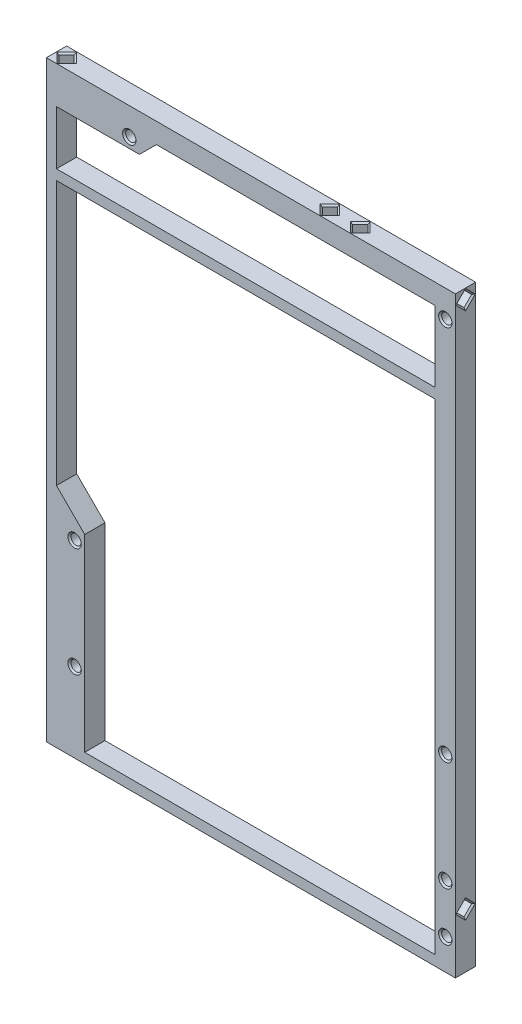
SolidWorks part; units mm, degrees
ref_plane "Front Plane" through (0, 0, 0) normal (0, 0, 1) x (1, 0, 0)
ref_plane "Top Plane" through (0, 0, 0) normal (0, 1, 0) x (1, 0, 0)
ref_plane "Right Plane" through (0, 0, 0) normal (1, 0, 0) x (0, 0, -1)
sketch "matx screw pattern" plane through (0, 0, 0) normal (0, 0, 1) x (1, 0, 0)
  line L1 (-121.92, 121.92) -> (121.92, 121.92) construction
  line L2 (-121.92, 121.92) -> (-121.92, -121.92) construction
  line L3 (-121.92, -121.92) -> (121.92, -121.92) construction
  line L4 (121.92, 121.92) -> (121.92, -121.92) construction
  point P4 (0, 121.92)
  point P6 (121.92, 0)
  point P7 (-111.76, -87.63)
  point P8 (-111.76, -41.91)
  point P9 (-88.9, 115.57)
  point P10 (43.18, -41.91)
  point P11 (43.18, -87.63)
  point P12 (43.18, -107.95)
  point P13 (115.57, -41.91)
  point P14 (115.57, 115.57)
  point P15 (43.18, 115.57)
  dimension "D1" = 243.84
  dimension "D2" = 10.16
  dimension "D3" = 22.86
  dimension "D4" = 227.33
  dimension "D5" = 154.94
  dimension "D6" = 203.2
  dimension "D7" = 45.72
  dimension "D8" = 20.32
  dimension "D9" = 34.29
sketch "Sketch1" plane through (0, 0, 0) normal (0, 0, 1) x (1, 0, 0)
  line L0 (-121.92, 121.92) -> (-121.92, -121.92) construction
  line L1 (-123.571, 126.8984) -> (47.4133, 126.8984)
  line L2 (-123.571, 126.8984) -> (-123.571, -120.7516)
  line L3 (-123.571, -120.7516) -> (47.4133, -120.7516)
  line L4 (47.4133, 126.8984) -> (47.4133, -120.7516)
  line L7 (-107.5267, -116.5183) -> (-107.5267, -37.6767)
  line L8 (-119.3377, 111.3367) -> (-84.6667, 111.3367)
  line L9 (38.9467, -116.5183) -> (38.9467, 84.5651)
  line L10 (-107.5267, -116.5183) -> (38.9467, -116.5183)
  line L11 (-107.5267, -37.6767) -> (-119.3377, -25.8657)
  line L12 (-119.3377, -25.8657) -> (-119.3377, 84.5651)
  line L13 (-84.6667, 111.3367) -> (-77.5716, 118.4317)
  line L14 (-77.5716, 118.4317) -> (38.9467, 118.4317)
  line L15 (-119.3377, 88.7984) -> (38.9467, 88.7984)
  line L16 (-119.3377, 84.5651) -> (38.9467, 84.5651)
  line L18 (-119.3377, 88.7984) -> (-119.3377, 111.3367)
  line L19 (38.9467, 88.7984) -> (38.9467, 118.4317)
  dimension "D1" = 4.9784
  dimension "D2" = 247.65
  dimension "D3" = 1.651
  dimension "D4" = 4.2333
  dimension "D5" = 4.2333
  dimension "D6" = 4.2333
  dimension "D7" = 8.4667
  dimension "D8" = 4.2333
  dimension "D9" = 4.2333
  dimension "D10" = 45
  dimension "D11" = 4.2333
  dimension "D12" = 8.4667
  dimension "D13" = 4.2333
  dimension "D14" = 45
  dimension "D15" = 4.2333
  dimension "D16" = 38.1
extrude "Boss-Extrude1" add sketch "Sketch1" against normal blind 8.4667 from offset 9.525 offset against normal yes
sketch "Sketch5" plane through (0, 0, -9.525) normal (0, 0, 1) x (1, 0, 0)
  point P0 (-88.9, 115.57)
  point P1 (43.18, 115.57)
  point P3 (43.18, -41.91)
  point P5 (43.18, -87.63)
  point P7 (43.18, -107.95)
  point P9 (-111.76, -87.63)
  point P11 (-111.76, -41.91)
hole_wizard "#18 (0.1695) Diameter Hole1" positions "Sketch5" profile "Sketch6" hole size "#18" standard "ANSI Inch" end condition through all
sketch "Sketch6" plane through (-88.9, 115.57, -9.525) normal (1, 0, 0) x (0, -1, 0)
  line L0 (0, 0) -> (0, 8.4667)
  line L1 (0, 8.4667) -> (2.1526, 8.4667)
  line L2 (2.1526, 8.4667) -> (2.1526, 0.635)
  line L3 (2.1526, 0.635) -> (2.7876, 0)
  line L5 (2.7876, 0) -> (0, 0)
  line L6 (-2.1526, 0.635) -> (-2.7876, 0) construction
  line L11 (0, -6.35) -> (0, 107.95) construction
  dimension "Thru Hole Dia." = 4.3053
  dimension "Thru Hole Depth" = 8.4667
  dimension "Near C'Sink Dia." = 5.5753
  dimension "Near C'Sink Angle" = 90
sketch "Sketch2" plane through (0, -120.7516, 0) normal (0, -1, 0) x (1, 0, 0)
  line L0 (-122.5127, -13.7583) -> (-119.3377, -10.5833)
  line L1 (-122.5127, -13.7583) -> (-119.3377, -16.9333)
  line L2 (-119.3377, -10.5833) -> (-116.1627, -13.7583)
  line L3 (-119.3377, -16.9333) -> (-116.1627, -13.7583)
  line L4 (-122.5127, -13.7583) -> (-116.1627, -13.7583) construction
  line L5 (-119.3377, -10.5833) -> (-119.3377, -16.9333) construction
  line L6 (40.005, -13.7583) -> (43.18, -10.5833)
  line L7 (40.005, -13.7583) -> (43.18, -16.9333)
  line L8 (43.18, -10.5833) -> (46.355, -13.7583)
  line L9 (43.18, -16.9333) -> (46.355, -13.7583)
  line L10 (40.005, -13.7583) -> (46.355, -13.7583) construction
  line L11 (43.18, -10.5833) -> (43.18, -16.9333) construction
  line L12 (-123.571, -17.9917) -> (-123.571, -9.525) construction
  line L16 (47.4133, -17.9917) -> (47.4133, -9.525) construction
  point P1 (-119.3377, -13.7583)
  point P2 (43.18, -13.7583)
  point P13 (47.4133, -13.7583)
  dimension "D1" = 6.35
  dimension "D2" = 4.2333
  dimension "D3" = 4.2333
extrude "bottom pins" cut sketch "Sketch2" against normal blind 6.35
sketch "Sketch3" plane through (-123.571, 0, 0) normal (-1, 0, 0) x (0, 0, 1)
  line L0 (-16.9333, 115.57) -> (-13.7583, 118.745)
  line L1 (-16.9333, 115.57) -> (-13.7583, 112.395)
  line L2 (-13.7583, 118.745) -> (-10.5833, 115.57)
  line L3 (-13.7583, 112.395) -> (-10.5833, 115.57)
  line L4 (-16.9333, 115.57) -> (-10.5833, 115.57) construction
  line L5 (-13.7583, 118.745) -> (-13.7583, 112.395) construction
  line L10 (-17.9917, 126.8984) -> (-17.9917, -120.7516) construction
  line L11 (-17.9917, 111.3367) -> (-9.525, 111.3367) construction
  point P1 (-13.7583, 115.57)
  dimension "D1" = 6.35
  dimension "D2" = 4.2333
  dimension "D3" = 4.2333
extrude "rear pins" cut sketch "Sketch3" against normal blind 6.35
sketch "Sketch4" plane through (47.4133, 0, 0) normal (1, 0, 0) x (0, 0, -1)
  line L0 (10.5833, 122.6651) -> (13.7583, 125.8401)
  line L1 (10.5833, 122.6651) -> (13.7583, 119.4901)
  line L2 (13.7583, 125.8401) -> (16.9333, 122.6651)
  line L3 (13.7583, 119.4901) -> (16.9333, 122.6651)
  line L4 (10.5833, 122.6651) -> (16.9333, 122.6651) construction
  line L5 (13.7583, 125.8401) -> (13.7583, 119.4901) construction
  line L6 (17.9917, 126.8984) -> (9.525, 126.8984) construction
  line L7 (17.9917, -120.7516) -> (9.525, -120.7516) construction
  line L10 (10.5833, -97.8916) -> (13.7583, -94.7166)
  line L11 (10.5833, -97.8916) -> (13.7583, -101.0666)
  line L12 (13.7583, -94.7166) -> (16.9333, -97.8916)
  line L13 (13.7583, -101.0666) -> (16.9333, -97.8916)
  line L14 (10.5833, -97.8916) -> (16.9333, -97.8916) construction
  line L15 (13.7583, -94.7166) -> (13.7583, -101.0666) construction
  point P1 (13.7583, 122.6651)
  point P3 (13.7583, 126.8984)
  dimension "D1" = 6.35
  dimension "D2" = 4.2333
  dimension "D3" = 22.86
extrude "front pins" cut sketch "Sketch4" against normal blind 6.35
sketch "Sketch7" plane through (0, 126.8984, 0) normal (0, 1, 0) x (1, 0, 0)
  line L0 (-6.096, 13.7583) -> (-9.271, 10.5833)
  line L1 (-6.096, 13.7583) -> (-9.271, 16.9333)
  line L2 (-9.271, 10.5833) -> (-12.446, 13.7583)
  line L3 (-9.271, 16.9333) -> (-12.446, 13.7583)
  line L4 (-6.096, 13.7583) -> (-12.446, 13.7583) construction
  line L5 (-9.271, 10.5833) -> (-9.271, 16.9333) construction
  line L6 (-116.1627, 13.7583) -> (-119.3377, 10.5833)
  line L7 (-116.1627, 13.7583) -> (-119.3377, 16.9333)
  line L8 (-119.3377, 10.5833) -> (-122.5127, 13.7583)
  line L9 (-119.3377, 16.9333) -> (-122.5127, 13.7583)
  line L10 (-116.1627, 13.7583) -> (-122.5127, 13.7583) construction
  line L11 (-119.3377, 10.5833) -> (-119.3377, 16.9333) construction
  line L18 (-123.571, 17.9917) -> (-123.571, 9.525) construction
  line L19 (0.254, 13.7583) -> (3.429, 16.9333)
  line L20 (0.254, 13.7583) -> (3.429, 10.5833)
  line L21 (3.429, 16.9333) -> (6.604, 13.7583)
  line L22 (3.429, 10.5833) -> (6.604, 13.7583)
  line L23 (0.254, 13.7583) -> (6.604, 13.7583) construction
  line L24 (3.429, 16.9333) -> (3.429, 10.5833) construction
  point P0 (-9.271, 13.7583)
  point P5 (-119.3377, 13.7583)
  point P20 (3.429, 13.7583)
  dimension "D1" = 6.35
  dimension "D2" = 4.2333
  dimension "D3" = 110.0667
  dimension "D5" = 12.7
extrude "Cut-Extrude1" cut sketch "Sketch7" against normal blind 6.35
chamfer "pin chamfers" distance 0.635 angle 45 64 edges at (47.4133, 121.0776, -15.3458) (47.4133, 124.2526, -15.3458) (47.4133, 124.2526, -12.1708) (47.4133, 121.0776, -12.1708) (41.5925, -114.4016, -12.1708) (44.7675, -114.4016, -12.1708) (44.7675, -114.4016, -15.3458) (41.5925, -114.4016, -15.3458) (41.0633, 124.2526, -12.1708) (41.0633, 124.2526, -15.3458) (41.0633, 121.0776, -15.3458) (41.0633, 121.0776, -12.1708) (-120.9252, -114.4016, -12.1708) (-117.7502, -114.4016, -12.1708) (-117.7502, -114.4016, -15.3458) (-120.9252, -114.4016, -15.3458) (-117.221, 117.1575, -15.3458) (-117.221, 117.1575, -12.1708) (-117.221, 113.9825, -12.1708) (-117.221, 113.9825, -15.3458) (41.5925, -120.7516, -15.3458) (44.7675, -120.7516, -15.3458) (44.7675, -120.7516, -12.1708) (41.5925, -120.7516, -12.1708) (-117.7502, -120.7516, -15.3458) (-117.7502, -120.7516, -12.1708) (-120.9252, -120.7516, -15.3458) (-120.9252, -120.7516, -12.1708) (-123.571, 113.9825, -12.1708) (-123.571, 117.1575, -12.1708) (-123.571, 113.9825, -15.3458) (-123.571, 117.1575, -15.3458) (41.0633, -96.3041, -12.1708) (41.0633, -96.3041, -15.3458) (41.0633, -99.4791, -15.3458) (41.0633, -99.4791, -12.1708) (47.4133, -99.4791, -15.3458) (47.4133, -99.4791, -12.1708) (47.4133, -96.3041, -12.1708) (47.4133, -96.3041, -15.3458) (1.8415, 120.5484, -15.3458) (5.0165, 120.5484, -15.3458) (5.0165, 120.5484, -12.1708) (1.8415, 120.5484, -12.1708) (-7.6835, 120.5484, -12.1708) (-10.8585, 120.5484, -12.1708) (-10.8585, 120.5484, -15.3458) (-7.6835, 120.5484, -15.3458) (-117.7502, 120.5484, -12.1708) (-120.9252, 120.5484, -12.1708) (-120.9252, 120.5484, -15.3458) (-117.7502, 120.5484, -15.3458) (-120.9252, 126.8984, -12.1708) (-120.9252, 126.8984, -15.3458) (-117.7502, 126.8984, -15.3458) (-117.7502, 126.8984, -12.1708) (-10.8585, 126.8984, -12.1708) (-10.8585, 126.8984, -15.3458) (-7.6835, 126.8984, -15.3458) (-7.6835, 126.8984, -12.1708) (1.8415, 126.8984, -12.1708) (5.0165, 126.8984, -12.1708) (5.0165, 126.8984, -15.3458) (1.8415, 126.8984, -15.3458)
